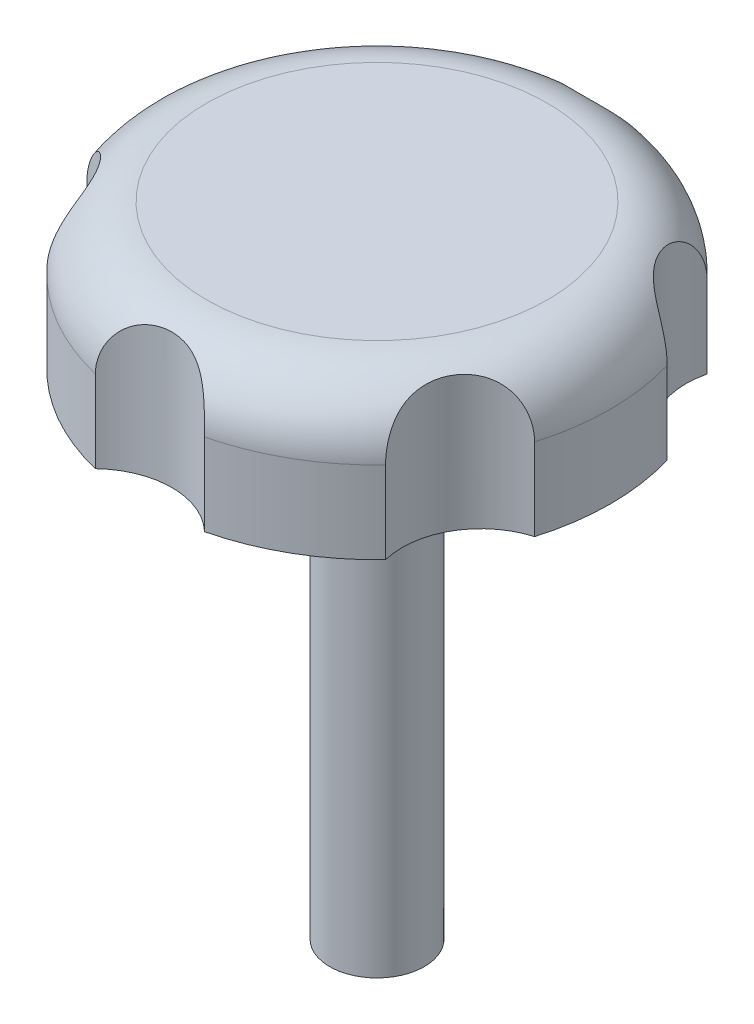
SolidWorks part; units mm, degrees
material "PF"
ref_plane "Спереди" through (0, 0, 0) normal (0, 0, 1) x (1, 0, 0)
ref_plane "Сверху" through (0, 0, 0) normal (0, 1, 0) x (1, 0, 0)
ref_plane "Справа" through (0, 0, 0) normal (1, 0, 0) x (0, 0, -1)
sketch "Эскиз1" plane through (0, 0, 0) normal (0, 1, 0) x (1, 0, 0)
  circle A0 centre (0, 0) radius 7.35
  dimension "D1" = 14.7
extrude "Бобышка-Вытянуть1" add sketch "Эскиз1" along normal blind 3.3
sketch "Эскиз2" plane through (0, 0, 0) normal (0, -1, 0) x (1, 0, 0)
  circle A1 centre (0, 0) radius 3
  dimension "D1" = 6
extrude "резьба" add sketch "Эскиз2" along normal blind 28
sketch "Эскиз3" plane through (0, 3.3, 0) normal (0, 1, 0) x (1, 0, 0)
  circle A0 centre (0, 0) radius 14.8
  dimension "D1" = 29.6
extrude "Бобышка-Вытянуть3" add sketch "Эскиз3" along normal blind 9.2
fillet "Скругление1" radius 4 1 edges at (0, 12.5, 14.8)
sketch "Эскиз4" plane through (0, 12.5, 0) normal (0, 1, 0) x (1, 0, 0)
  line L0 (0, 0) -> (0, 18) construction
  circle A0 centre (0, 18) radius 5
  circle A1 centre (15.5885, 9) radius 5
  circle A2 centre (15.5885, -9) radius 5
  circle A3 centre (0, -18) radius 5
  circle A4 centre (-15.5885, -9) radius 5
  circle A5 centre (-15.5885, 9) radius 5
  point P12 (0, 0)
  dimension "D1" = 10
  dimension "D2" = 18
  dimension "D3" = 6
extrude "Вырез-Вытянуть1" cut sketch "Эскиз4" against normal blind 10
sketch "Эскиз5" plane through (0, 12.5, 0) normal (0, 1, 0) x (1, 0, 0)
  circle A0 centre (0, 0) radius 7.4
  dimension "D1" = 14.8
extrude "Вырез-Вытянуть2" [suppressed] cut sketch "Эскиз5" against normal blind 0.2
